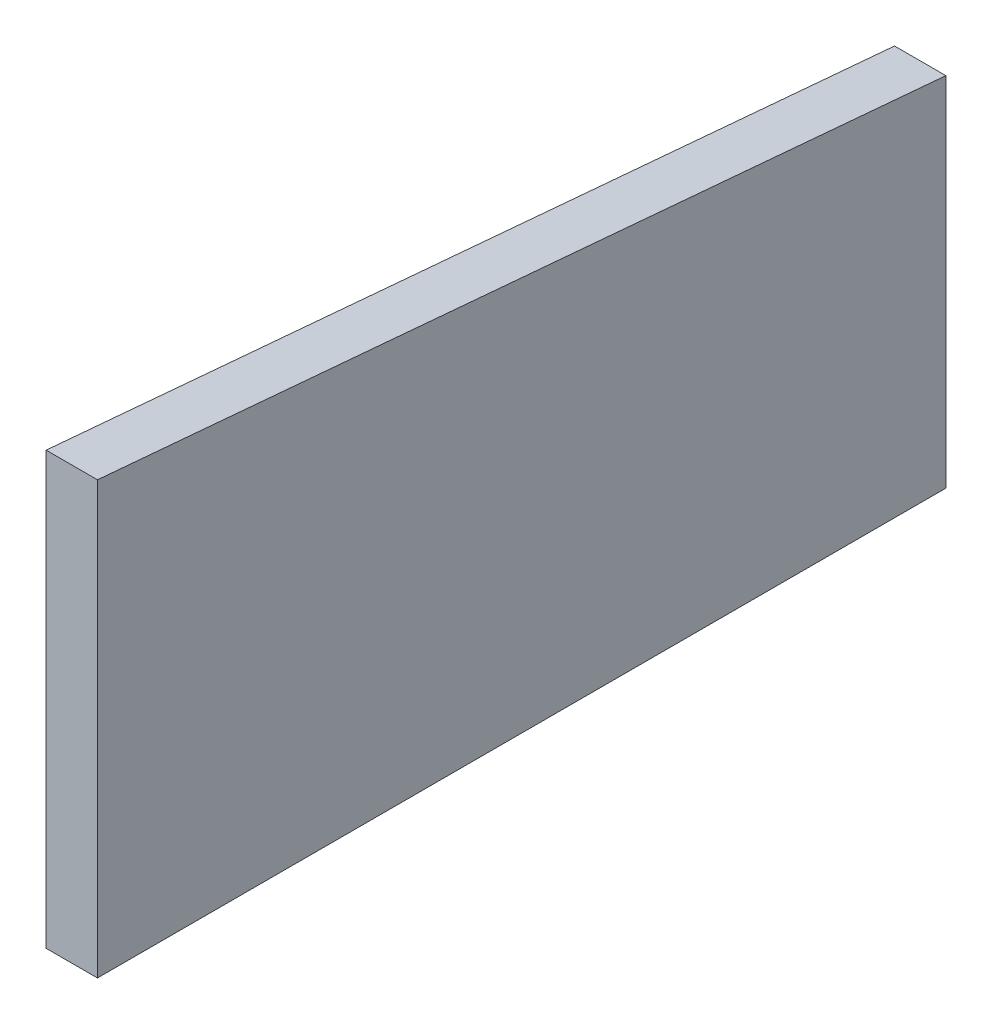
SolidWorks part; units mm, degrees
material "Pine"
ref_plane "Front Plane" through (0, 0, 0) normal (0, 0, 1) x (1, 0, 0)
ref_plane "Top Plane" through (0, 0, 0) normal (0, 1, 0) x (1, 0, 0)
ref_plane "Right Plane" through (0, 0, 0) normal (1, 0, 0) x (0, 0, -1)
sketch "Sketch1" plane through (0, 0, 0) normal (1, 0, 0) x (0, 0, -1)
  line L0 (0, 0) -> (301.625, 0)
  line L1 (0, 0) -> (0, 153.3888)
  line L2 (0, 153.3888) -> (301.625, 127)
  line L3 (301.625, 127) -> (301.625, 0)
  dimension "D1" = 85
  dimension "D2" = 127
  dimension "D3" = 301.625
  dimension "D4" = 153.3888
extrude "Boss-Extrude1" add sketch "Sketch1" along normal blind 18.2562
